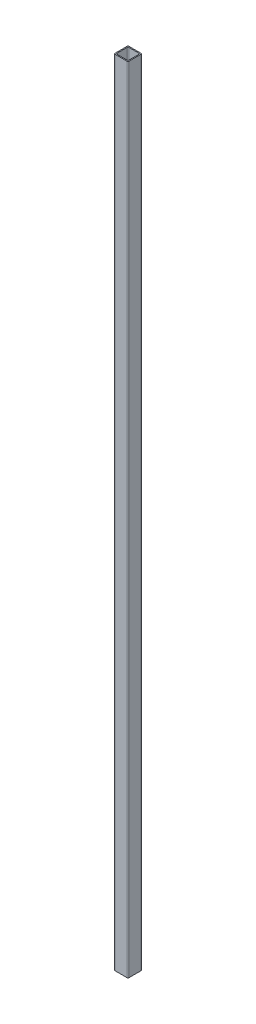
SolidWorks part; units mm, degrees
material "1.0037 (S235JR)"
ref_plane "Plan de face" through (0, 0, 0) normal (0, 0, 1) x (1, 0, 0)
ref_plane "Plan de dessus" through (0, 0, 0) normal (0, 1, 0) x (1, 0, 0)
ref_plane "Plan de droite" through (0, 0, 0) normal (1, 0, 0) x (0, 0, -1)
sketch "Esquisse1" plane through (0, 0, 0) normal (1, 0, 0) x (0, 0, -1)
  line L0 (0, 0) -> (0, 2000)
  dimension "D1" = 2000
other "Custom TUBE-CARRE-35-2.5(1)"
ref_plane "Plan1" through (0, 0, 0) normal (0, 1, 0) x (0, 0, 1)
sketch "Esquisse11" plane through (0, 0, 0) normal (0, 1, 0) x (0, 0, 1)
  line L1 (-13, -15) -> (13, -15)
  line L2 (-15, -13) -> (-15, 13)
  line L3 (-13, 15) -> (13, 15)
  line L4 (15, -13) -> (15, 13)
  line L5 (-15, -15) -> (15, 15) construction
  line L6 (-15, 15) -> (15, -15) construction
  line L7 (-15.5, -17.5) -> (15.5, -17.5)
  line L8 (-17.5, -15.5) -> (-17.5, 15.5)
  line L9 (-15.5, 17.5) -> (15.5, 17.5)
  line L10 (17.5, -15.5) -> (17.5, 15.5)
  line L11 (-17.5, -17.5) -> (17.5, 17.5) construction
  line L12 (-17.5, 17.5) -> (17.5, -17.5) construction
  arc A0 (15.5, -17.5) -> (17.5, -15.5) centre (15.5, -15.5) ccw
  arc A1 (13, -15) -> (15, -13) centre (13, -13) ccw
  arc A2 (-13, -15) -> (-15, -13) centre (-13, -13) cw
  arc A3 (-15.5, -17.5) -> (-17.5, -15.5) centre (-15.5, -15.5) cw
  arc A4 (15.5, 17.5) -> (17.5, 15.5) centre (15.5, 15.5) cw
  arc A5 (13, 15) -> (15, 13) centre (13, 13) cw
  arc A6 (-15, 13) -> (-13, 15) centre (-13, 13) cw
  arc A7 (-17.5, 15.5) -> (-15.5, 17.5) centre (-15.5, 15.5) cw
  point P0 (0, 0)
  point P6 (0, 0)
  point P35 (0, 17.5)
  point P36 (0, 15)
  point P37 (-15, 0)
  point P38 (-17.5, 0)
  point P39 (0, -15)
  point P40 (0, -17.5)
  point P41 (15, 0)
  point P42 (17.5, 0)
  point P43 (0, 0)
  dimension "D5" = 2
  dimension "D1" = 2.5
  dimension "D2" = 35
  dimension "D3" = 35
  dimension "D4" = 2.5
